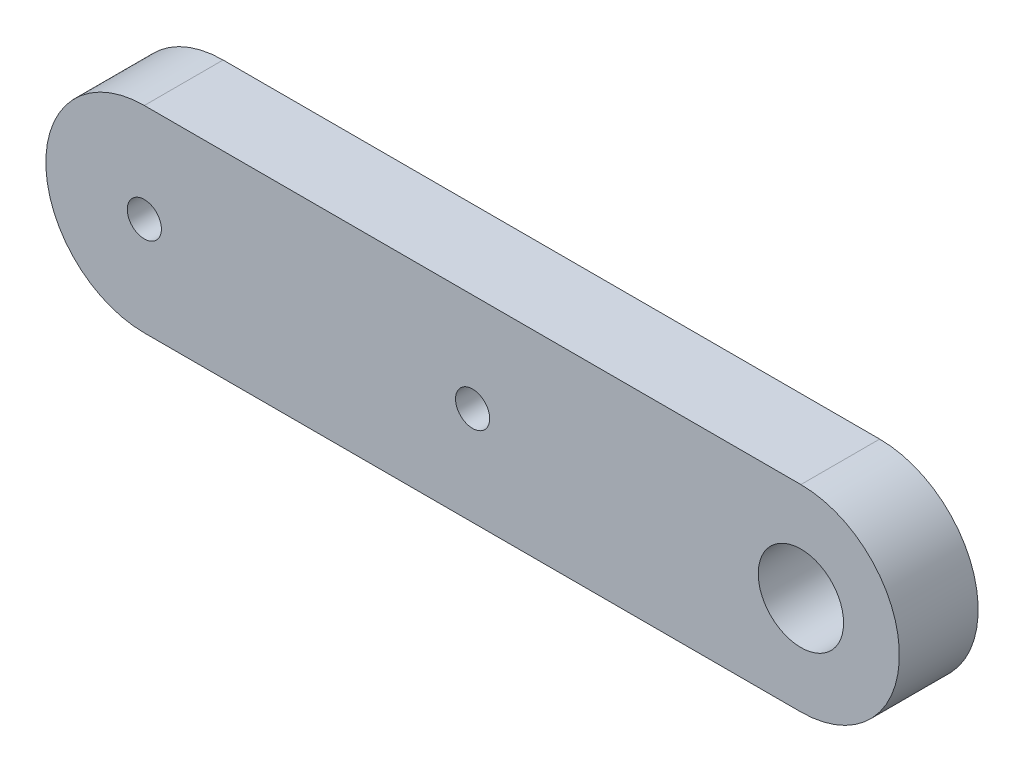
SolidWorks part; units mm, degrees
material "Pine"
ref_plane "Front Plane" through (0, 0, 0) normal (0, 0, 1) x (1, 0, 0)
ref_plane "Top Plane" through (0, 0, 0) normal (0, 1, 0) x (1, 0, 0)
ref_plane "Right Plane" through (0, 0, 0) normal (1, 0, 0) x (0, 0, -1)
sketch "Sketch1" plane through (0, 0, 0) normal (0, 0, 1) x (1, 0, 0)
  line L0 (0, 7.5) -> (50, 7.5)
  line L1 (50, -7.5) -> (0, -7.5)
  circle A0 centre (0, 0) radius 7.5
  circle A1 centre (50, 0) radius 7.5
  dimension "D1" = 50
  dimension "D2" = 15
extrude "Boss-Extrude1" add sketch "Sketch1" along normal blind 6 contours A1 L0 A0 L1 | A1 | A0
ref_plane "Plane1" through (0, 0, 3) normal (0, 0, 1) x (1, 0, 0)
sketch "Sketch2" plane through (0, 0, 6) normal (0, 0, 1) x (1, 0, 0)
  circle A0 centre (0, 0) radius 1.3
  circle A1 centre (50, 0) radius 1.3
  dimension "D1" = 2.6
extrude "Cut-Extrude1" cut sketch "Sketch2" against normal through all
pattern_linear "LPattern1" count 4 spacing 25 along (1, 0, 0) of "Cut-Extrude1"
sketch "Sketch3" plane through (0, 0, 6) normal (0, 0, 1) x (1, 0, 0)
  circle A0 centre (50, 0) radius 3.25
  dimension "D1" = 6.5
extrude "Cut-Extrude2" cut sketch "Sketch3" against normal through all
